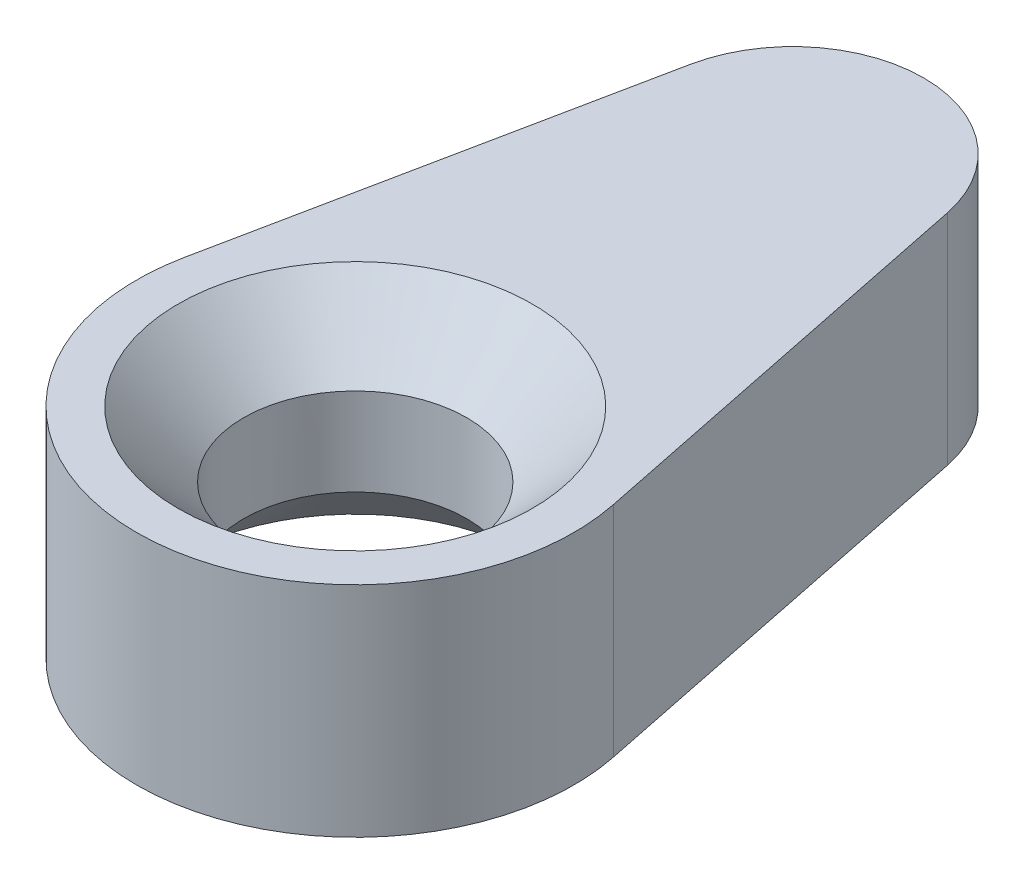
SolidWorks part; units mm, degrees
ref_plane "Front Plane" through (0, 0, 0) normal (0, 0, 1) x (1, 0, 0)
ref_plane "Top Plane" through (0, 0, 0) normal (0, 1, 0) x (1, 0, 0)
ref_plane "Right Plane" through (0, 0, 0) normal (1, 0, 0) x (0, 0, -1)
sketch "Sketch1" plane through (0, 0, 0) normal (0, 1, 0) x (1, 0, 0)
  line L0 (-12.4434, 2.54) -> (-7.466, 26.924)
  line L1 (7.466, 26.924) -> (12.4434, 2.54)
  circle A0 centre (0, 0) radius 6.477
  circle A1 centre (0, 0) radius 12.7
  arc A2 (-7.466, 26.924) -> (7.466, 26.924) centre (0, 25.4) cw
  dimension "D1" = 12.954
  dimension "D2" = 7.62
  dimension "D3" = 25.4
  dimension "D4" = 25.4
extrude "Boss-Extrude1" add sketch "Sketch1" along normal blind 12.7 contours A2 L0 A1 L1 | A1 A0
chamfer "Chamfer1" distance 3.81 angle 45 2 edges at (0, 12.7, 6.477) (0, 0, 6.477)
